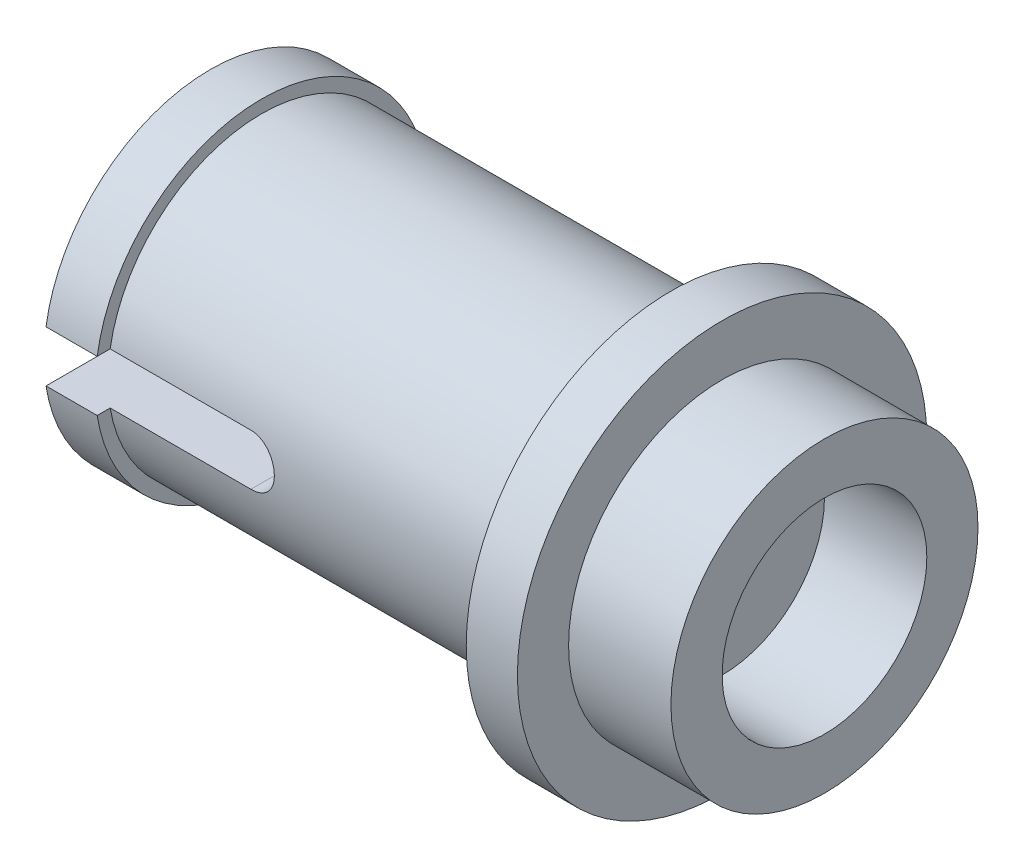
SolidWorks part; units mm, degrees
ref_plane "Front Plane" through (0, 0, 0) normal (0, 0, 1) x (1, 0, 0)
ref_plane "Top Plane" through (0, 0, 0) normal (0, 1, 0) x (1, 0, 0)
ref_plane "Right Plane" through (0, 0, 0) normal (1, 0, 0) x (0, 0, -1)
sketch "Sketch1" plane through (0, 0, 0) normal (0, 0, 1) x (1, 0, 0)
  line L0 (-5, 2.4) -> (-5, 0)
  line L1 (-5, 0) -> (-0.8, 0)
  line L2 (-0.8, 0) -> (-0.8, 2.4)
  line L3 (-0.8, 2.4) -> (-5, 2.4)
  line L4 (-5, 0) -> (-0.8, 0) construction
revolve "Revolve1" add sketch "Sketch1" angle 360 about L4
hole_wizard "Ø0.8 (0.8) Diameter Hole1" positions "3DSketch1" profile "Sketch2" hole size "Ø0.8" standard "ANSI Metric"
sketch3d "3DSketch1"
  point P0 (-5, 0, -2.4)
sketch "Sketch2" plane through (-5, 0, -2.4) normal (1, 0, 0) x (0, 1, 0)
  line L0 (0, 0) -> (0, 4.8)
  line L1 (0, 4.8) -> (0.4, 4.8)
  line L2 (0.4, 4.8) -> (0.4, 0)
  line L5 (0.4, 0) -> (0, 0)
  line L11 (0, -6.35) -> (0, 107.95) construction
  dimension "Thru Hole Dia." = 0.8
  dimension "Thru Hole Depth" = 4.8
ref_plane "Plane1" through (-0.8, 0, 0) normal (-1, 0, 0) x (0, 0, 1)
sketch "Sketch6" plane through (-0.8, 0, 0) normal (-1, 0, 0) x (0, 0, 1)
  circle A0 centre (0, 0) radius 3.2
extrude "Boss-Extrude1" add sketch "Sketch6" against normal blind 0.8
sketch "Sketch7" plane through (-5, 0, 0) normal (-1, 0, 0) x (0, 0, 1)
  line L0 (-2.569, -0.4) -> (2.569, -0.4)
  arc A0 (2.569, -0.4) -> (-2.569, -0.4) centre (0, 0) cw
extrude "Boss-Extrude2" add sketch "Sketch7" along normal blind 3
sketch "Sketch8" plane through (-5, 0, 0) normal (1, 0, 0) x (0, 0, -1)
  line L0 (2.569, -0.4) -> (2.3664, -0.4)
  line L1 (-2.3664, -0.4) -> (-2.569, -0.4)
  arc A0 (2.3664, -0.4) -> (-2.3664, -0.4) centre (0, 0) cw
  arc A1 (-2.569, -0.4) -> (2.569, -0.4) centre (0, 0) ccw
extrude "Cut-Extrude1" cut sketch "Sketch8" against normal blind 2.2
sketch "Sketch9" plane through (-5, 0, 0) normal (-1, 0, 0) x (0, 0, 1)
  line L0 (2.3664, 0.4) -> (-2.3664, 0.4)
  arc A0 (-2.3664, 0.4) -> (2.3664, 0.4) centre (0, 0) cw
extrude "Boss-Extrude3" add sketch "Sketch9" along normal blind 2.2
sketch "Sketch10" plane through (-7.2, 0, 0) normal (-1, 0, 0) x (0, 0, 1)
  line L0 (2.569, 0.4) -> (-2.569, 0.4)
  arc A0 (-2.569, 0.4) -> (2.569, 0.4) centre (0, 0) cw
extrude "Boss-Extrude4" add sketch "Sketch10" along normal blind 0.8
sketch "Sketch11" plane through (0, 0, 0) normal (1, 0, 0) x (0, 0, -1)
  circle A0 centre (0, 0) radius 2.4
extrude "Boss-Extrude5" add sketch "Sketch11" along normal blind 1.6
ref_plane "Plane2" through (0, 0, 0) normal (0, 0, -1) x (-1, 0, 0)
sketch "Sketch16" plane through (0, 0, 0) normal (0, 0, -1) x (-1, 0, 0)
  line L0 (0.8, 1.6) -> (0.8, 0)
  line L1 (0.8, 0) -> (8, 0)
  line L2 (8, 0) -> (8, 1.6)
  line L3 (8, 1.6) -> (0.8, 1.6)
  line L4 (0.8, 0) -> (8, 0) construction
revolve "Cut-Revolve1" cut sketch "Sketch16" angle 360 about L1
hole_wizard "Ø3.2 (3.2) Diameter Hole1" positions "Sketch18" profile "Sketch17" hole size "Ø3.2" standard "ANSI Metric"
sketch "Sketch18" plane through (1.6, 0, 0) normal (1, 0, 0) x (0, 0, -1)
  point P0 (0, 0)
sketch "Sketch17" plane through (1.6, 0, 0) normal (0, 1, 0) x (0, 0, -1)
  line L0 (0, 0) -> (0, 1.6)
  line L1 (0, 1.6) -> (1.6, 1.6)
  line L2 (1.6, 1.6) -> (1.6, 0)
  line L5 (1.6, 0) -> (0, 0)
  line L10 (0, 1.6) -> (-1.6, 1.6) construction
  line L11 (0, -6.35) -> (0, 107.95) construction
  dimension "Hole Dia." = 3.2
  dimension "Hole Depth" = 1.6
  dimension "Drill Angle" = 180
